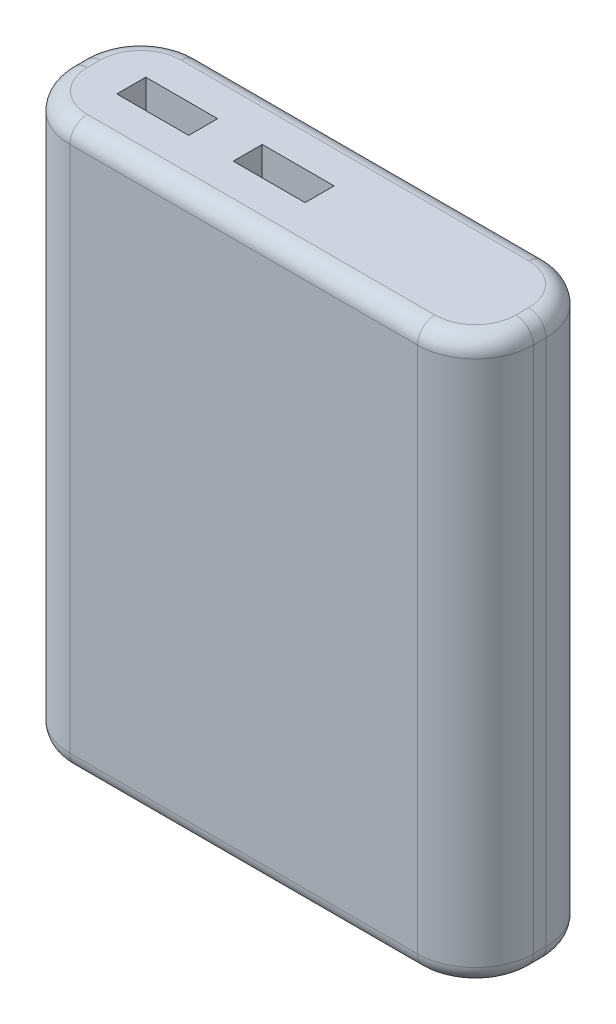
SolidWorks part; units mm, degrees
ref_plane "Front Plane" through (0, 0, 0) normal (0, 0, 1) x (1, 0, 0)
ref_plane "Top Plane" through (0, 0, 0) normal (0, 1, 0) x (1, 0, 0)
ref_plane "Right Plane" through (0, 0, 0) normal (1, 0, 0) x (0, 0, -1)
sketch "Sketch1" plane through (0, 0, 0) normal (0, 1, 0) x (1, 0, 0)
  line L1 (-30, 11.1) -> (30, 11.1)
  line L2 (-40, 1.1) -> (-40, -1.1)
  line L3 (-30, -11.1) -> (30, -11.1)
  line L4 (40, 1.1) -> (40, -1.1)
  line L5 (-40, 11.1) -> (40, -11.1) construction
  line L6 (-40, -11.1) -> (40, 11.1) construction
  arc A0 (30, -11.1) -> (40, -1.1) centre (30, -1.1) ccw
  arc A1 (30, 11.1) -> (40, 1.1) centre (30, 1.1) cw
  arc A2 (-40, -1.1) -> (-30, -11.1) centre (-30, -1.1) ccw
  arc A3 (-30, 11.1) -> (-40, 1.1) centre (-30, 1.1) ccw
  point P0 (0, 0)
  dimension "D3" = 10
  dimension "D1" = 80
  dimension "D2" = 22.2
extrude "Boss-Extrude1" add sketch "Sketch1" along normal blind 97
fillet "Fillet1" radius 3 16 edges at (0, 97, 11.1) (-37.0711, 97, 8.1711) (-40, 97, 0) (-37.0711, 97, -8.1711) (0, 97, -11.1) (37.0711, 97, -8.1711) (40, 97, 0) (37.0711, 97, 8.1711) (40, 0, 0) (37.0711, 0, -8.1711) (0, 0, -11.1) (-37.0711, 0, -8.1711) (-40, 0, 0) (-37.0711, 0, 8.1711) (0, 0, 11.1) (37.0711, 0, 8.1711)
sketch "Sketch2" plane through (0, 97, 0) normal (0, 1, 0) x (1, 0, 0)
  line L0 (-37, 0) -> (37, 0) construction
  line L1 (-37, 1.1) -> (-37, -1.1) construction
  line L2 (37, -1.1) -> (37, 1.1) construction
  line L3 (-40, -1.1) -> (-40, 1.1) construction
  line L4 (-30.5, 2.5) -> (-18.1, 2.5)
  line L5 (-30.5, 2.5) -> (-30.5, -2.5)
  line L6 (-30.5, -2.5) -> (-18.1, -2.5)
  line L7 (-18.1, 2.5) -> (-18.1, -2.5)
  line L8 (-30.5, 2.5) -> (-18.1, -2.5) construction
  line L9 (-30.5, -2.5) -> (-18.1, 2.5) construction
  line L10 (-10.4, 2.5) -> (2, 2.5)
  line L11 (-10.4, 2.5) -> (-10.4, -2.5)
  line L12 (-10.4, -2.5) -> (2, -2.5)
  line L13 (2, 2.5) -> (2, -2.5)
  line L14 (-10.4, 2.5) -> (2, -2.5) construction
  line L15 (-10.4, -2.5) -> (2, 2.5) construction
  point P6 (-24.3, 0)
  point P11 (-4.2, 0)
  dimension "D1" = 12.4
  dimension "D2" = 12.4
  dimension "D3" = 5
  dimension "D4" = 5
  dimension "D5" = 9.5
  dimension "D6" = 7.7
extrude "Cut-Extrude1" cut sketch "Sketch2" against normal blind 10
